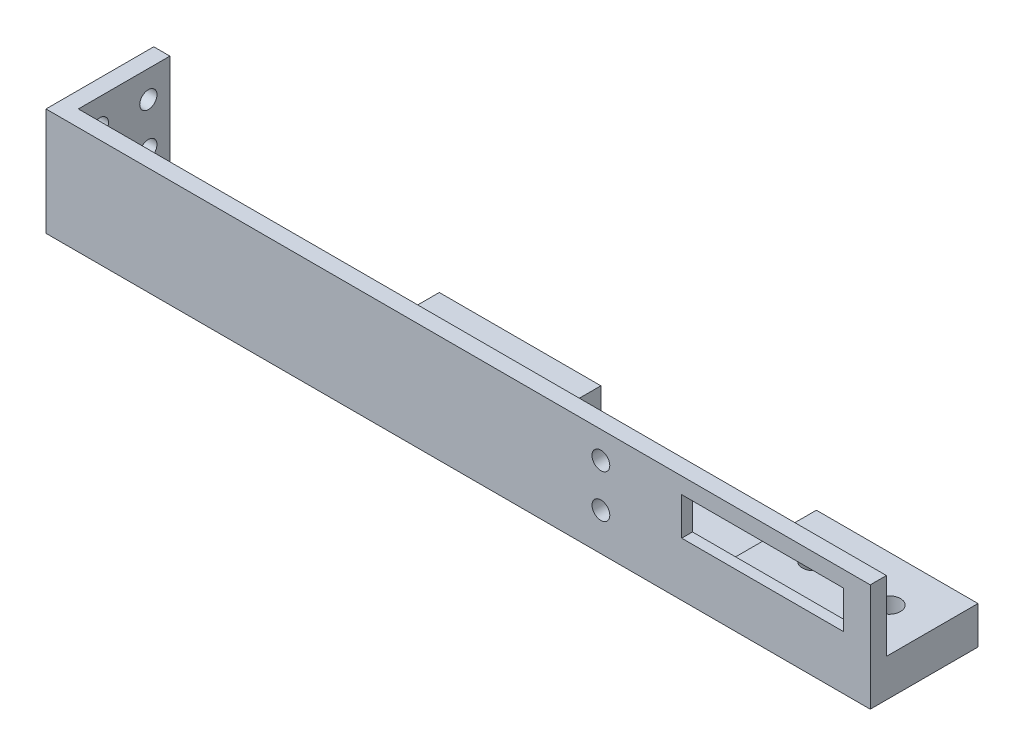
SolidWorks part; units mm, degrees
ref_plane "Front Plane" through (0, 0, 0) normal (0, 0, 1) x (1, 0, 0)
ref_plane "Top Plane" through (0, 0, 0) normal (0, 1, 0) x (1, 0, 0)
ref_plane "Right Plane" through (0, 0, 0) normal (1, 0, 0) x (0, 0, -1)
sketch "Sketch1" plane through (0, 0, 0) normal (0, 0, 1) x (1, 0, 0)
  line L1 (88.4016, -22.1754) -> (241.4016, -22.1754)
  line L2 (88.4016, -22.1754) -> (88.4016, -42.1754)
  line L3 (88.4016, -42.1754) -> (241.4016, -42.1754)
  line L4 (241.4016, -22.1754) -> (241.4016, -42.1754)
  dimension "D1" = 20
  dimension "D2" = 153
extrude "Boss-Extrude1" add sketch "Sketch1" along normal blind 3
sketch "Sketch2" plane through (0, 0, 0) normal (0, 0, -1) x (-1, 0, 0)
  line L0 (-88.4016, -42.1754) -> (-241.4016, -42.1754) construction
  line L1 (-88.4016, -22.1754) -> (-91.4016, -22.1754)
  line L2 (-88.4016, -22.1754) -> (-88.4016, -42.1754)
  line L3 (-88.4016, -42.1754) -> (-91.4016, -42.1754)
  line L4 (-91.4016, -22.1754) -> (-91.4016, -42.1754)
  dimension "D1" = 3
extrude "Boss-Extrude2" add sketch "Sketch2" along normal blind 17
sketch "Sketch3" plane through (0, 0, 0) normal (0, 0, -1) x (-1, 0, 0)
  line L0 (-241.4016, -42.1754) -> (-241.4016, -22.1754) construction
  line L1 (-91.4016, -42.1754) -> (-241.4016, -42.1754)
  line L2 (-91.4016, -42.1754) -> (-91.4016, -39.1754)
  line L3 (-91.4016, -39.1754) -> (-241.4016, -39.1754)
  line L4 (-241.4016, -42.1754) -> (-241.4016, -39.1754)
  dimension "D1" = 3
extrude "Boss-Extrude3" add sketch "Sketch3" along normal blind 17
sketch "Sketch4" plane through (88.4016, 0, 0) normal (-1, 0, 0) x (0, 0, 1)
  circle A0 centre (-13, -27.1754) radius 1.6
  circle A1 centre (-4, -27.1754) radius 1.6
  circle A2 centre (-4, -35.1754) radius 1.6
  circle A3 centre (-13, -35.1754) radius 1.5984
extrude "Cut-Extrude1" cut sketch "Sketch4" against normal blind 10
sketch "Sketch6" plane through (0, -39.1754, 0) normal (0, 1, 0) x (1, 0, 0)
  line L0 (241.4016, 0) -> (91.4016, 0) construction
  line L1 (241.4016, 17) -> (211.4016, 17)
  line L2 (241.4016, 17) -> (241.4016, 0)
  line L3 (241.4016, 0) -> (211.4016, 0)
  line L4 (211.4016, 17) -> (211.4016, 0)
  dimension "D1" = 30
extrude "Boss-Extrude4" add sketch "Sketch6" along normal blind 4
sketch "Sketch7" plane through (0, -35.1754, 0) normal (0, 1, 0) x (1, 0, 0)
  line L0 (241.4016, 17) -> (211.4016, 17) construction
  line L1 (241.4016, 0) -> (241.4016, 17) construction
  circle A0 centre (219.4016, 8.5) radius 2.1
  circle A1 centre (233.4016, 8.5) radius 2.1
  dimension "D1" = 4.2
  dimension "D2" = 4.2
  dimension "D3" = 8.5
  dimension "D4" = 8.5
  dimension "D5" = 8
  dimension "D6" = 22
extrude "Cut-Extrude3" cut sketch "Sketch7" against normal through all
sketch "Sketch8" plane through (0, -42.1754, 0) normal (0, -1, 0) x (1, 0, 0)
  circle A0 centre (219.4016, -8.5) radius 4
  circle A1 centre (233.4016, -8.5) radius 4
  dimension "D1" = 8
  dimension "D2" = 8
extrude "Cut-Extrude4" cut sketch "Sketch8" against normal blind 2.5
sketch "Sketch9" plane through (0, -39.1754, 0) normal (0, 1, 0) x (1, 0, 0)
  line L0 (91.4016, 17) -> (211.4016, 17) construction
  line L1 (141.4016, 17) -> (171.4016, 17)
  line L2 (141.4016, 17) -> (141.4016, 0)
  line L3 (141.4016, 0) -> (171.4016, 0)
  line L4 (171.4016, 17) -> (171.4016, 0)
  line L5 (241.4016, 0) -> (91.4016, 0) construction
  line L6 (241.4016, 0) -> (241.4016, 17) construction
  dimension "D1" = 70
  dimension "D2" = 30
extrude "Boss-Extrude5" add sketch "Sketch9" along normal up to surface (4 mm away) up to face at (219.4016, -35.1754, -6.4)
sketch "Sketch12" plane through (0, -35.1754, 0) normal (0, 1, 0) x (1, 0, 0)
  line L0 (171.4016, 17) -> (171.4016, 0) construction
  line L1 (141.4016, 0) -> (141.4016, 17) construction
  line L2 (241.4016, 0) -> (91.4016, 0) construction
  circle A0 centre (163.4016, 8.5) radius 2.1
  circle A1 centre (149.4016, 8.5) radius 2.1
  dimension "D1" = 4.2
  dimension "D2" = 4.2
  dimension "D3" = 8
  dimension "D4" = 8
  dimension "D5" = 8.5
  dimension "D6" = 8.5
extrude "Cut-Extrude7" cut sketch "Sketch12" against normal through all
sketch "Sketch13" plane through (0, -42.1754, 0) normal (0, -1, 0) x (1, 0, 0)
  circle A0 centre (163.4016, -8.5) radius 4
  circle A1 centre (149.4016, -8.5) radius 4
  dimension "D1" = 8
  dimension "D2" = 8
extrude "Cut-Extrude8" cut sketch "Sketch13" against normal blind 2.5
sketch "Sketch14" plane through (0, 0, 3) normal (0, 0, 1) x (1, 0, 0)
  line L0 (241.4016, -42.1754) -> (241.4016, -22.1754) construction
  line L1 (236.4016, -25.1754) -> (206.4016, -25.1754)
  line L2 (236.4016, -25.1754) -> (236.4016, -32.1754)
  line L3 (236.4016, -32.1754) -> (206.4016, -32.1754)
  line L4 (206.4016, -25.1754) -> (206.4016, -32.1754)
  line L5 (241.4016, -22.1754) -> (88.4016, -22.1754) construction
  dimension "D1" = 7
  dimension "D2" = 30
  dimension "D3" = 5
  dimension "D4" = 3
extrude "Cut-Extrude9" cut sketch "Sketch14" against normal blind 3
chamfer "Chamfer8" distance 1 angle 45 4 edges at (206.4016, -28.6754, 0) (221.4016, -32.1754, 0) (221.4016, -25.1754, 0) (236.4016, -28.6754, 0)
chamfer "Chamfer9" distance 3 angle 45 2 edges at (116.4016, -39.1754, 0) (191.4016, -39.1754, 0)
sketch "Sketch15" plane through (0, -39.1754, 0) normal (0, 1, 0) x (1, 0, 0)
  line L0 (171.4016, 17) -> (211.4016, 17) construction
  line L1 (211.4016, 0) -> (208.3016, 0)
  line L2 (211.4016, 0) -> (211.4016, 17)
  line L3 (211.4016, 17) -> (208.3016, 17)
  line L4 (208.3016, 0) -> (208.3016, 17)
  line L5 (91.4016, 17) -> (141.4016, 17) construction
  line L6 (174.5016, 17) -> (171.4016, 17)
  line L7 (174.5016, 17) -> (174.5016, 0)
  line L8 (174.5016, 0) -> (171.4016, 0)
  line L9 (171.4016, 17) -> (171.4016, 0)
  line L10 (138.3016, 17) -> (141.4016, 17)
  line L11 (138.3016, 17) -> (138.3016, 0)
  line L12 (138.3016, 0) -> (141.4016, 0)
  line L13 (141.4016, 17) -> (141.4016, 0)
  dimension "D1" = 3.1
  dimension "D2" = 3.1
  dimension "D3" = 3.1
extrude "Cut-Extrude10" cut sketch "Sketch15" along normal blind 3
sketch "Sketch16" plane through (0, 0, 0) normal (0, 0, -1) x (-1, 0, 0)
  line L0 (-241.4016, -22.1754) -> (-91.4016, -22.1754) construction
  line L1 (-206.4016, -32.1754) -> (-206.4016, -25.1754) construction
  circle A0 centre (-191.4016, -27.1754) radius 1.65
  circle A1 centre (-191.4016, -35.1754) radius 1.65
  dimension "D1" = 3.3
  dimension "D2" = 3.3
  dimension "D3" = 5
  dimension "D4" = 13
  dimension "D5" = 15
  dimension "D6" = 15
extrude "Cut-Extrude11" cut sketch "Sketch16" against normal up to surface (3 mm away) up to face at (221.4016, -28.6754, 3)
sketch "Sketch17" plane through (0, 0, 0) normal (0, 0, -1) x (-1, 0, 0)
  circle A0 centre (-191.4016, -35.1754) radius 3
  dimension "D1" = 6
extrude "Cut-Extrude12" cut sketch "Sketch17" along normal blind 6
